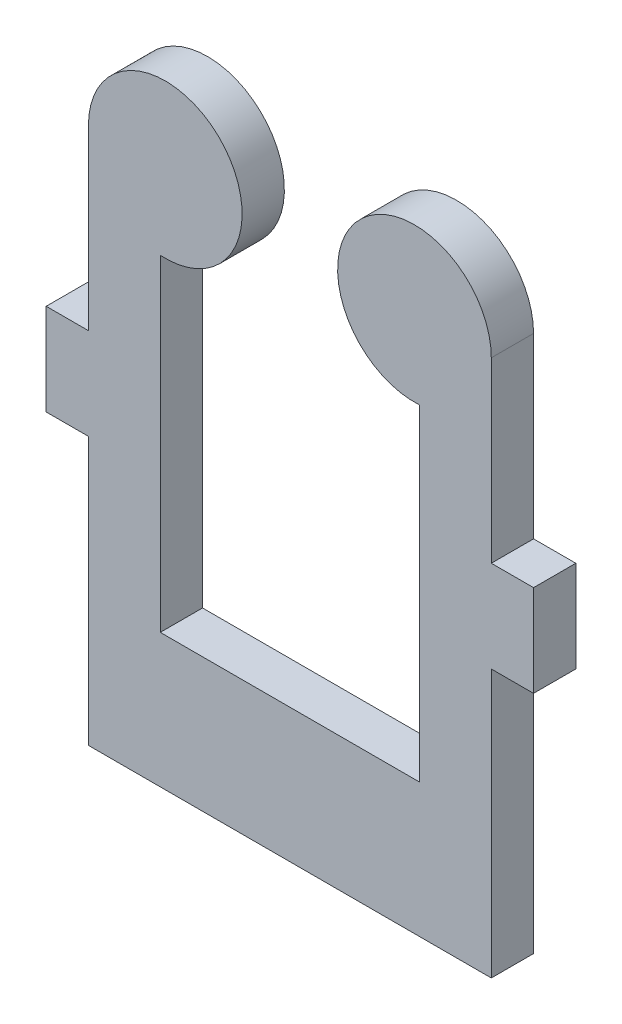
SolidWorks part; units mm, degrees
ref_plane "Front Plane" through (0, 0, 0) normal (0, 0, 1) x (1, 0, 0)
ref_plane "Top Plane" through (0, 0, 0) normal (0, 1, 0) x (1, 0, 0)
ref_plane "Right Plane" through (0, 0, 0) normal (1, 0, 0) x (0, 0, -1)
sketch "Front" plane through (0, 0, 0) normal (0, 0, 1) x (1, 0, 0)
  line L0 (-8.845, 33.13) -> (8.845, 33.13) construction
  line L1 (0, 33.13) -> (0, 0) construction
  line L3 (-2.6, -2.55) -> (2.6, -2.55) construction
  line L4 (-2.6, -2.55) -> (-2.6, 2.55) construction
  line L5 (-2.6, 2.55) -> (2.6, 2.55) construction
  line L6 (2.6, -2.55) -> (2.6, 2.55) construction
  line L7 (-2.6, -2.55) -> (2.6, 2.55) construction
  line L8 (-2.6, 2.55) -> (2.6, -2.55) construction
  line L9 (-11.2, 2.55) -> (11.2, 2.55) construction
  line L10 (-11.2, 2.55) -> (-11.2, 39.57) construction
  line L11 (-11.2, 39.57) -> (11.2, 39.57) construction
  line L12 (11.2, 2.55) -> (11.2, 39.57) construction
  line L13 (-11.2, 2.55) -> (11.2, 39.57) construction
  line L14 (-11.2, 39.57) -> (11.2, 2.55) construction
  circle A0 centre (0, 0) radius 1.5
  circle A1 centre (-8.845, 33.13) radius 1.5
  circle A2 centre (8.845, 33.13) radius 1.5
  circle A3 centre (0, 14.45) radius 5 construction
  point P8 (0, 21.06)
  point P17 (0, 1.5)
  dimension "D1" = 3
  dimension "D2" = 3
  dimension "D3" = 3
  dimension "D11" = 10
  dimension "D4" = 33.13
  dimension "D5" = 17.69
  dimension "D6" = 5.1
  dimension "D7" = 5.2
  dimension "D8" = 37.02
  dimension "D9" = 22.4
  dimension "D10" = 1.05
  dimension "D12" = 11.9
sketch "Bottom" plane through (0, 0, 0) normal (0, 1, 0) x (1, 0, 0)
  line L1 (-11.2, -9.55) -> (11.2, -9.55) construction
  line L2 (-11.2, -9.55) -> (-11.2, 9.55) construction
  line L3 (-11.2, 9.55) -> (11.2, 9.55) construction
  line L4 (11.2, -9.55) -> (11.2, 9.55) construction
  line L5 (-11.2, -9.55) -> (11.2, 9.55) construction
  line L6 (-11.2, 9.55) -> (11.2, -9.55) construction
  point P0 (0, 0)
  point P6 (39.318, 9.55)
  dimension "D1" = 19.1
  dimension "D2" = 22.4
sketch "Side" plane through (0, 0, 0) normal (1, 0, 0) x (0, 0, -1)
  line L0 (0, 34.63) -> (0, 31.63) construction
  line L1 (0, 2.55) -> (0, 39.57) construction
  line L2 (0, -2.55) -> (0, 2.55) construction
  line L3 (0, 1.5) -> (0, -1.5) construction
  line L4 (9.55, 0) -> (-9.55, 0) construction
  line L5 (0, 34.63) -> (0, 31.63) construction
  line L6 (0, 2.55) -> (0, 39.57) construction
  line L7 (0, -2.55) -> (0, 2.55) construction
  line L8 (0, 1.5) -> (0, -1.5) construction
  line L9 (9.55, 0) -> (-9.55, 0) construction
  line L10 (-1.4, -2.55) -> (-1.4, 2.55) construction
  line L11 (-1.4, -2.55) -> (1.4, -2.55) construction
  line L12 (-1.4, 2.55) -> (1.4, 2.55) construction
  line L13 (1.4, -2.55) -> (1.4, 2.55) construction
  line L14 (-1.4, -2.55) -> (1.4, 2.55) construction
  line L15 (-1.4, 2.55) -> (1.4, -2.55) construction
  line L16 (-9.55, 2.55) -> (-9.55, 0) construction
  line L17 (-9.55, 39.57) -> (9.55, 39.57) construction
  line L18 (-9.55, 39.57) -> (-9.55, 2.55) construction
  line L19 (-9.55, 2.55) -> (9.55, 2.55) construction
  line L20 (9.55, 39.57) -> (9.55, 2.55) construction
  line L21 (-9.55, 39.57) -> (9.55, 2.55) construction
  line L22 (-9.55, 2.55) -> (9.55, 39.57) construction
  line L23 (9.55, 2.55) -> (9.55, 0) construction
  point P0 (0, 21.06)
  point P7 (0, 21.06)
  point P12 (0, 0)
  dimension "D1" = 2.8
ref_plane "motorFace" through (0, 0, 9.55) normal (0, 0, 1) x (1, 0, 0)
sketch "Sketch5" plane through (0, 0, 9.55) normal (0, 0, 1) x (1, 0, 0)
  line L0 (9.2, 4.5) -> (-9.2, 4.5)
  line L1 (-9.2, 4.5) -> (-9.2, 27.6866)
  line L3 (-14.3, 33.13) -> (-14.3, 20.5)
  line L4 (-14.3, -5) -> (14.3, -5)
  line L5 (0, 4.5) -> (0, -5) construction
  line L6 (-11.2, 2.55) -> (-11.2, 39.57) construction
  line L7 (-11.2, 0) -> (11.2, 0) construction
  line L8 (-14.3, 14) -> (-14.3, 20.5) construction
  line L9 (-17.3, 14) -> (-17.3, 20.5)
  line L10 (-14.3, 20.5) -> (-17.3, 20.5)
  line L11 (-14.3, 14) -> (-17.3, 14)
  line L12 (-14.3, 20.5) -> (-14.3, 14) construction
  line L13 (-14.3, 14) -> (-14.3, -5)
  line L14 (14.3, 20.5) -> (14.3, 14) construction
  line L15 (14.3, 14) -> (14.3, 20.5) construction
  line L16 (14.3, 14) -> (14.3, -5)
  line L17 (14.3, 14) -> (17.3, 14)
  line L18 (14.3, 20.5) -> (17.3, 20.5)
  line L19 (17.3, 14) -> (17.3, 20.5)
  line L20 (14.3, 33.13) -> (14.3, 20.5)
  line L21 (9.2, 4.5) -> (9.2, 27.6866)
  arc A0 (-9.2, 27.6866) -> (-14.3, 33.13) centre (-8.845, 33.13) ccw
  arc A1 (-14.3, 33.13) -> (-9.2, 27.6866) centre (-8.845, 33.13) ccw construction
  arc A2 (14.3, 33.13) -> (9.2, 27.6866) centre (8.845, 33.13) cw construction
  arc A3 (9.2, 27.6866) -> (14.3, 33.13) centre (8.845, 33.13) cw
  point P1 (-14.5858, 20.565)
  point P13 (0, 0)
  dimension "D5" = 3
  dimension "D1" = 3.1
  dimension "D2" = 2
  dimension "D3" = 5
  dimension "D4" = 4.5
  dimension "D6" = 6.5
  dimension "D7" = 14
extrude "Base" add sketch "Sketch5" along normal blind 3 from offset 3
equation "\"3mmThruHole\"= 3"
equation "\"TabLength\"= 5.2"
equation "\"TabThick\"= 2.8"
equation "\"TabHeight\"= 5.10"
equation "\"D1@Front\" = \"3mmThruHole\""
equation "\"D2@Front\" = \"3mmThruHole\""
equation "\"D3@Front\" = \"3mmThruHole\""
equation "\"D6@Front\" = \"TabHeight\""
equation "\"D7@Front\" = \"TabLength\""
equation "\"D1@Side\" = \"TabThick\""
